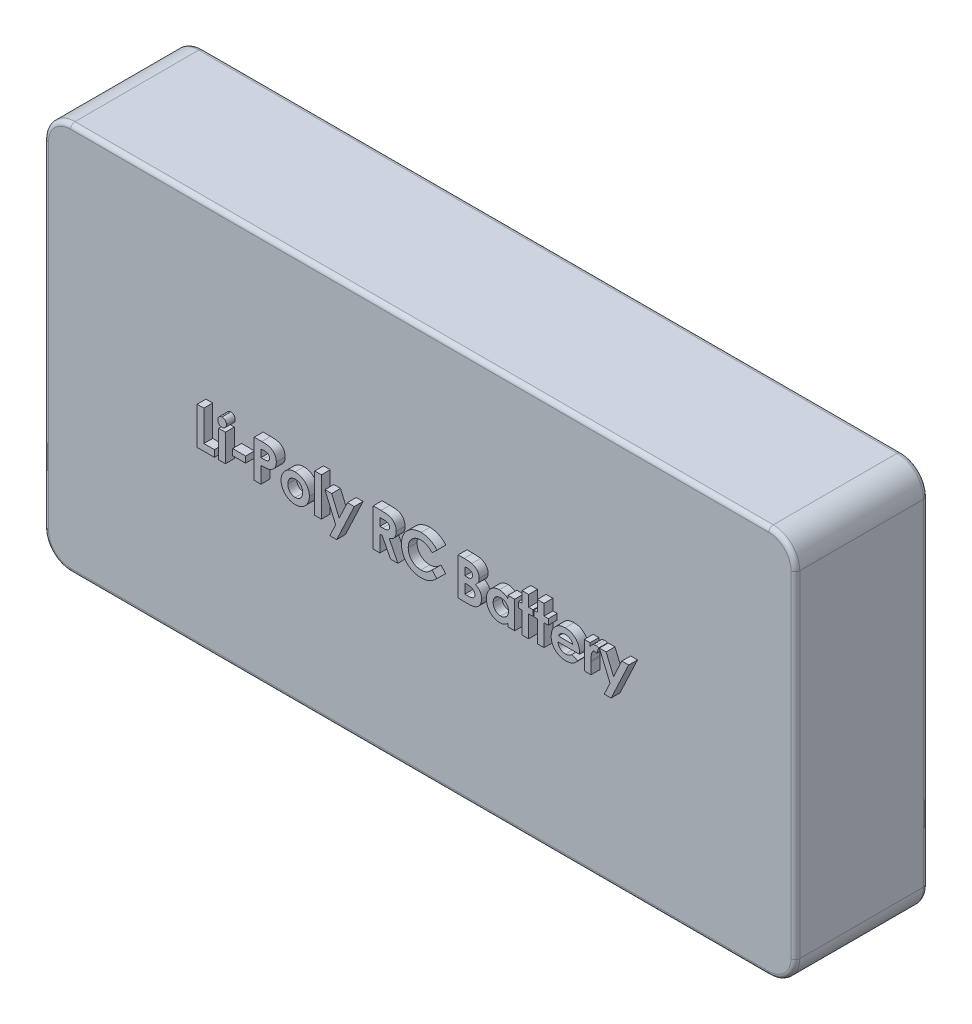
SolidWorks part; units mm, degrees
ref_plane "Front Plane" through (0, 0, 0) normal (0, 0, 1) x (1, 0, 0)
ref_plane "Top Plane" through (0, 0, 0) normal (0, 1, 0) x (1, 0, 0)
ref_plane "Right Plane" through (0, 0, 0) normal (1, 0, 0) x (0, 0, -1)
sketch "Sketch1" plane through (0, 0, 0) normal (0, 0, 1) x (1, 0, 0)
  line L1 (-35.1174, 12.3044) -> (49.8826, 12.3044)
  line L2 (-35.1174, 12.3044) -> (-35.1174, -31.6956)
  line L3 (-35.1174, -31.6956) -> (49.8826, -31.6956)
  line L4 (49.8826, 12.3044) -> (49.8826, -31.6956)
  dimension "D1" = 85
  dimension "D2" = 44
extrude "Boss-Extrude1" add sketch "Sketch1" along normal blind 15
fillet "Fillet1" radius 3 4 edges at (49.8826, 12.3044, 7.5) (49.8826, -31.6956, 7.5) (-35.1174, -31.6956, 7.5) (-35.1174, 12.3044, 7.5)
fillet "Fillet2" radius 0.5 16 edges at (49.0039, 11.4257, 0) (49.8826, -9.6956, 0) (49.0039, -30.8169, 0) (7.3826, -31.6956, 0) (-34.2387, -30.8169, 0) (-35.1174, -9.6956, 0) (-34.2387, 11.4257, 0) (49.0039, 11.4257, 15) (49.8826, -9.6956, 15) (49.0039, -30.8169, 15) (7.3826, -31.6956, 15) (-34.2387, -30.8169, 15) (-35.1174, -9.6956, 15) (-34.2387, 11.4257, 15) (7.3826, 12.3044, 0) (7.3826, 12.3044, 15)
sketch "Sketch2" plane through (0, 0, 15) normal (0, 0, 1) x (1, 0, 0)
  line L0 (-34.6174, -11.207) -> (49.3826, -11.207) construction
  line L1 (-34.6174, 9.3044) -> (-34.6174, -28.6956) construction
  line L2 (49.3826, -28.6956) -> (49.3826, 9.3044) construction
  text T0 "Li-Poly RC Battery" font "Century Gothic" height in points 16
extrude "Boss-Extrude2" add sketch "Sketch2" along normal blind 1
